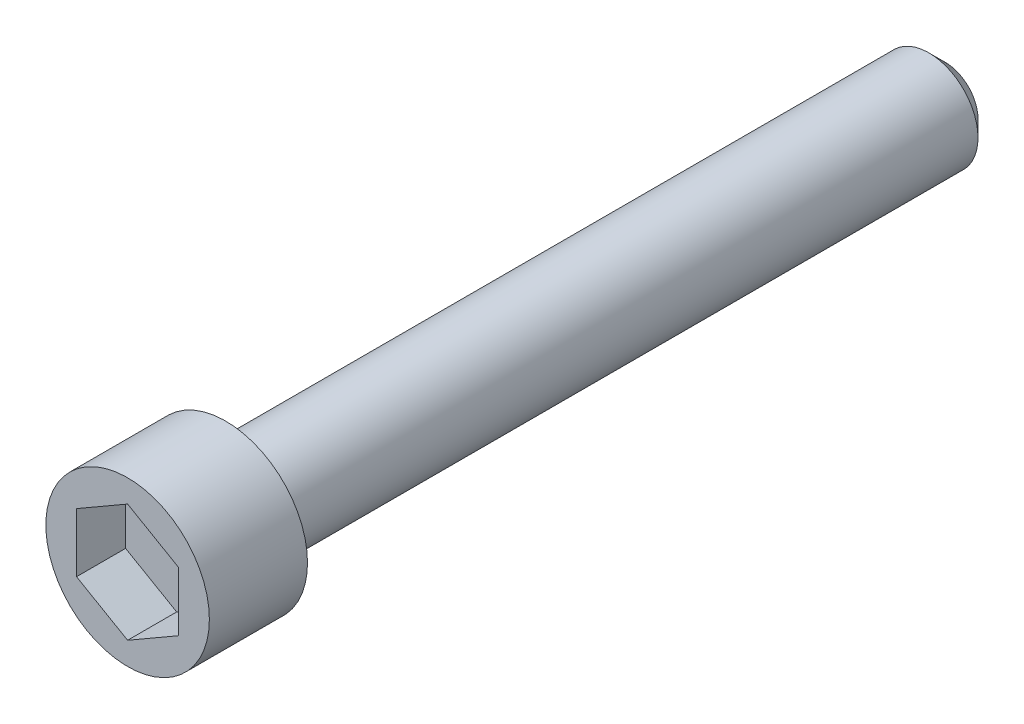
SolidWorks part; units mm, degrees
ref_plane "前视基准面" through (0, 0, 0) normal (0, 0, 1) x (1, 0, 0)
ref_plane "上视基准面" through (0, 0, 0) normal (0, 1, 0) x (1, 0, 0)
ref_plane "右视基准面" through (0, 0, 0) normal (1, 0, 0) x (0, 0, -1)
sketch "草图1" plane through (0, 0, 0) normal (0, 0, 1) x (1, 0, 0)
  circle A0 centre (0, 0) radius 1.5
extrude "凸台-拉伸1" add sketch "草图1" along normal blind 22
sketch "草图2" plane through (0, 0, 22) normal (0, 0, 1) x (1, 0, 0)
  circle A0 centre (0, 0) radius 2.5
extrude "凸台-拉伸2" add sketch "草图2" along normal blind 3
sketch "草图3" plane through (0, 0, 25) normal (0, 0, 1) x (1, 0, 0)
  line L1 (0, 1.8034) -> (-1.5618, 0.9017)
  line L2 (-1.5618, 0.9017) -> (-1.5618, -0.9017)
  line L3 (-1.5618, -0.9017) -> (0, -1.8034)
  line L4 (0, -1.8034) -> (1.5618, -0.9017)
  line L5 (1.5618, -0.9017) -> (1.5618, 0.9017)
  line L6 (1.5618, 0.9017) -> (0, 1.8034)
  circle A0 centre (0, 0) radius 1.5618 construction
extrude "切除-拉伸1" cut sketch "草图3" against normal blind 1.5
chamfer "倒角1" distance 0.5 angle 45 1 edges at (1.5, 0, 0)
